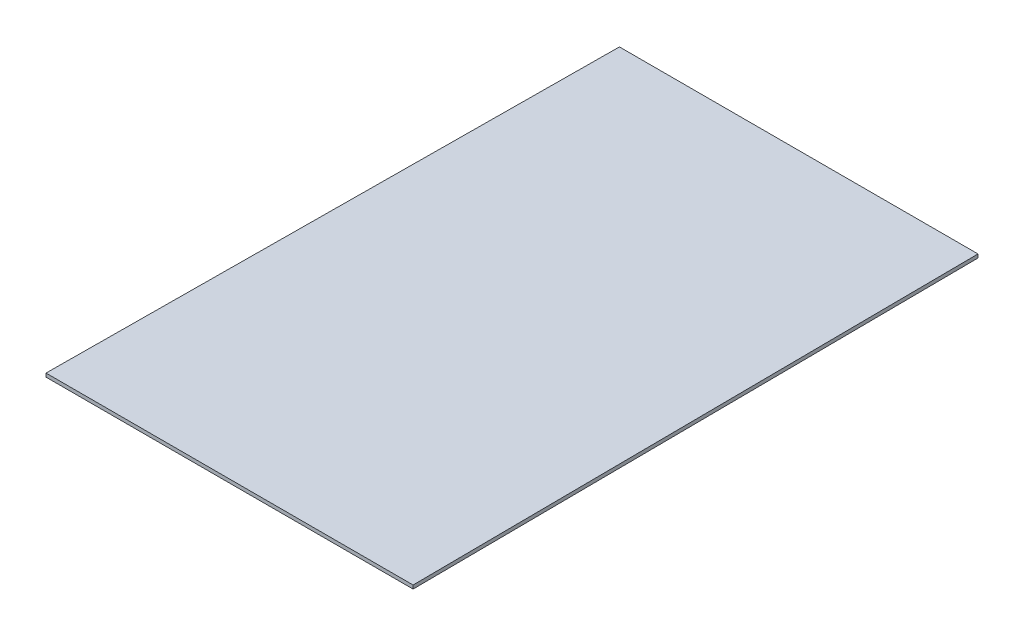
SolidWorks part; units mm, degrees
material "ABS"
ref_plane "Front" through (0, 0, 0) normal (0, 0, 1) x (1, 0, 0)
ref_plane "Top" through (0, 0, 0) normal (0, 1, 0) x (1, 0, 0)
ref_plane "Right" through (0, 0, 0) normal (1, 0, 0) x (0, 0, -1)
sketch "Sketch1" plane through (0, 0, 0) normal (0, 1, 0) x (1, 0, 0)
  line L0 (-163.83, 0) -> (163.83, 0)
  line L1 (0, 0) -> (0, 508) construction
  line L2 (-160.02, 508) -> (160.02, 508)
  line L3 (-160.02, 508) -> (-163.83, 0)
  line L4 (160.02, 508) -> (163.83, 0)
  dimension "D1" = 327.66
  dimension "D2" = 320.04
  dimension "D3" = 508
extrude "Boss-Extrude1" add sketch "Sketch1" along normal blind 3.175
